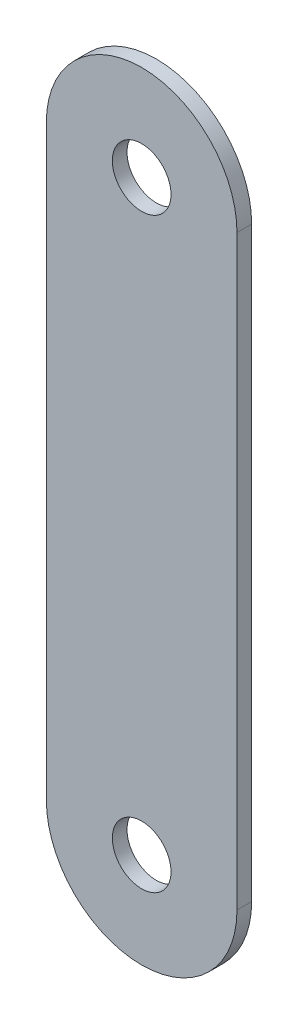
SolidWorks part; units mm, degrees
ref_plane "前视基准面" through (0, 0, 0) normal (0, 0, 1) x (1, 0, 0)
ref_plane "上视基准面" through (0, 0, 0) normal (0, 1, 0) x (1, 0, 0)
ref_plane "右视基准面" through (0, 0, 0) normal (1, 0, 0) x (0, 0, -1)
sketch "草图1" plane through (0, 0, 0) normal (0, 0, 1) x (1, 0, 0)
  line L0 (0, -20) -> (0, 20) construction
  line L1 (-6.5, -20) -> (-6.5, 20)
  line L2 (6.5, -20) -> (6.5, 20)
  arc A0 (-6.5, -20) -> (6.5, -20) centre (0, -20) ccw
  arc A1 (6.5, 20) -> (-6.5, 20) centre (0, 20) ccw
  point P2 (0, 0)
  dimension "D2" = 6.5
  dimension "D1" = 40
extrude "凸台-拉伸1" add sketch "草图1" along normal blind 1
sketch "草图2" plane through (0, 0, 1) normal (0, 0, 1) x (1, 0, 0)
  circle A0 centre (0, -20) radius 2
  circle A1 centre (0, 20) radius 2
  dimension "D1" = 4
  dimension "D2" = 4
extrude "切除-拉伸1" cut sketch "草图2" against normal through all
